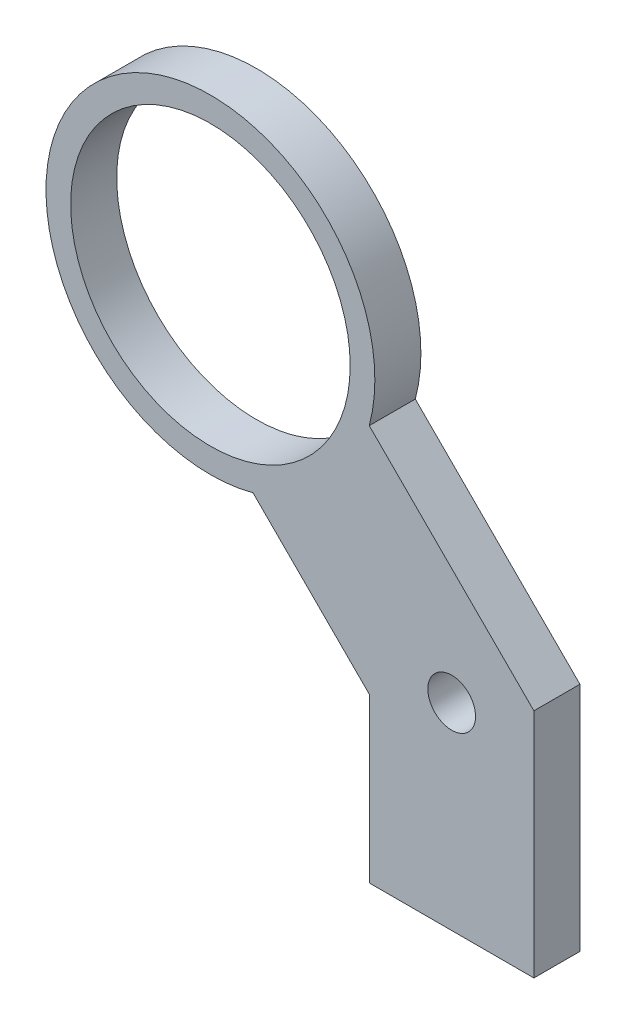
SolidWorks part; units mm, degrees
ref_plane "Front Plane" through (0, 0, 0) normal (0, 0, 1) x (1, 0, 0)
ref_plane "Top Plane" through (0, 0, 0) normal (0, 1, 0) x (1, 0, 0)
ref_plane "Right Plane" through (0, 0, 0) normal (1, 0, 0) x (0, 0, -1)
sketch "Sketch1" plane through (0, 0, 0) normal (0, 0, 1) x (1, 0, 0)
  line L0 (0, 0) -> (-29.3449, 29.3449) construction
  line L1 (0, 0) -> (0, 31.0325) construction
  line L2 (-10, -4.1421) -> (-10, -24)
  line L3 (-10, -24) -> (10, -24)
  line L4 (10, -24) -> (10, 4.1421)
  line L5 (0, 0) -> (0, -24) construction
  line L6 (10, 4.1421) -> (-10.0264, 24.1686)
  line L7 (-10, -4.1421) -> (-24.1686, 10.0264)
  line L8 (7.0711, 7.0711) -> (-22.2739, 36.416) construction
  line L9 (-7.0711, -7.0711) -> (-36.416, 22.2739) construction
  circle A0 centre (0, 0) radius 2.9
  arc A1 (-10.0264, 24.1686) -> (-24.1686, 10.0264) centre (-29.3449, 29.3449) ccw
  dimension "D1" = 5.8
  dimension "D3" = 40
  dimension "D2" = 41.5
  dimension "D4" = 45
  dimension "D5" = 24
  dimension "D6" = 20
  dimension "D7" = 10
  dimension "D8" = 10
extrude "Boss-Extrude1" add sketch "Sketch1" along normal blind 5.6
sketch "Sketch2" plane through (0, 0, 5.6) normal (0, 0, 1) x (1, 0, 0)
  circle A0 centre (-29.3449, 29.3449) radius 17
  dimension "D1" = 34
extrude "Cut-Extrude1" cut sketch "Sketch2" against normal through all
equation "\"smallPulleyTeeth\"= 15"
equation "\"largePulleyTeeth\"= 30"
equation "\"eighthThick\"= 2.9mm"
equation "\"sixteenthThick\" = 1.7mm"
equation "\"wheelEighthThick\"=3.0mm"
equation "\"quarterThick\"=5.6mm"
equation "\"OD\" = 150mm"
equation "\"puckAngle\" = 60.5deg"
equation "\"puckDiam\" = 76.5mm"
equation "\"axlePress\" = 5.8mm"
equation "\"D1@Sketch1\"=\"axlePress\""
equation "\"D1@Boss-Extrude1\"=\"quarterThick\""
